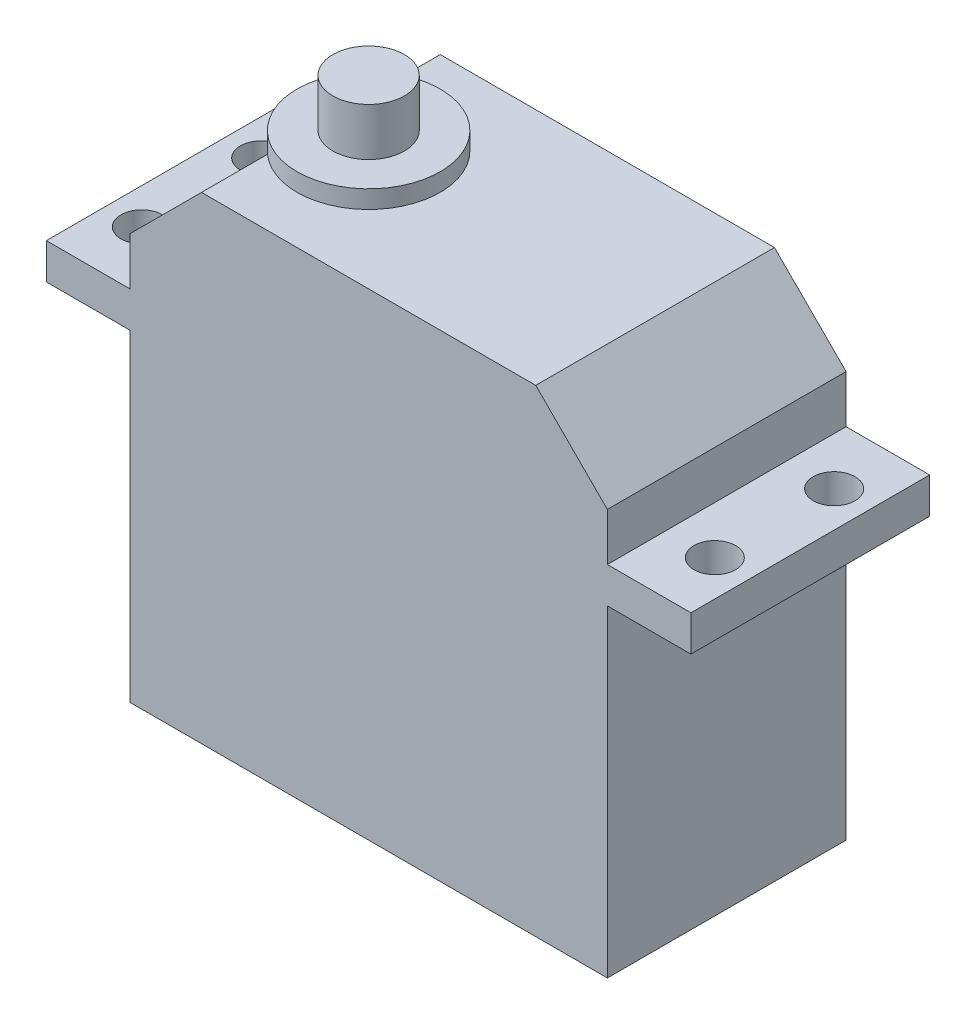
SolidWorks part; units mm, degrees
ref_plane "前视基准面" through (0, 0, 0) normal (0, 0, 1) x (1, 0, 0)
ref_plane "上视基准面" through (0, 0, 0) normal (0, 1, 0) x (1, 0, 0)
ref_plane "右视基准面" through (0, 0, 0) normal (1, 0, 0) x (0, 0, -1)
other "Configuration Table"
sketch "草图1" plane through (0, 0, 0) normal (0, 0, 1) x (1, 0, 0)
  line L1 (0, 0) -> (40, 0)
  line L2 (0, 0) -> (0, 40)
  line L3 (0, 40) -> (40, 40)
  line L4 (40, 0) -> (40, 40)
  dimension "D1" = 40
  dimension "D2" = 40
extrude "凸台-拉伸1" add sketch "草图1" along normal mid plane 20
sketch "草图2" plane through (0, 0, 0) normal (0, 0, 1) x (1, 0, 0)
  line L0 (0, 0) -> (40, 0) construction
  line L1 (-7, 30) -> (47, 30)
  line L2 (-7, 30) -> (-7, 27)
  line L3 (-7, 27) -> (47, 27)
  line L4 (47, 30) -> (47, 27)
  line L5 (40, 40) -> (0, 40) construction
  point P8 (20, 40)
  point P9 (20, 30)
  dimension "D1" = 27
  dimension "D2" = 3
  dimension "D3" = 54
extrude "凸台-拉伸2" add sketch "草图2" along normal mid plane 20
chamfer "倒角1" distance 6 angle 45 2 edges at (40, 40, 0) (0, 40, 0)
sketch "草图4" plane through (0, 40, 0) normal (0, 1, 0) x (1, 0, 0)
  line L0 (34, 10) -> (6, 10) construction
  circle A0 centre (10, 0) radius 6
  point P4 (20, 10)
  dimension "D1" = 12
  dimension "D2" = 10
extrude "凸台-拉伸3" add sketch "草图4" along normal blind 1.5 and the other way blind 20
sketch "草图5" plane through (0, 41.5, 0) normal (0, 1, 0) x (1, 0, 0)
  circle A0 centre (10, 0) radius 3
  dimension "D1" = 6
extrude "凸台-拉伸4" add sketch "草图5" along normal blind 4
sketch "草图6" plane through (0, 30, 0) normal (0, 1, 0) x (1, 0, 0)
  line L0 (34, 10) -> (6, 10) construction
  circle A0 centre (-4, 5) radius 1.75
  circle A1 centre (-4, -5) radius 1.75
  circle A2 centre (44, 5) radius 1.75
  circle A3 centre (44, -5) radius 1.75
  point P15 (20, 10)
  dimension "D1" = 3.5
  dimension "D2" = 10
  dimension "D3" = 5
  dimension "D4" = 48
  dimension "D5" = 24
extrude "切除-拉伸1" cut sketch "草图6" against normal through all
sketch "草图7" plane through (0, 0, -10) normal (0, 0, -1) x (-1, 0, 0)
  line L0 (0, 27) -> (0, 0) construction
  line L1 (-40, 0) -> (0, 0)
  line L2 (-40, 0) -> (-40, 12)
  line L3 (-40, 12) -> (0, 12)
  line L4 (0, 0) -> (0, 12)
  dimension "D1" = 12
